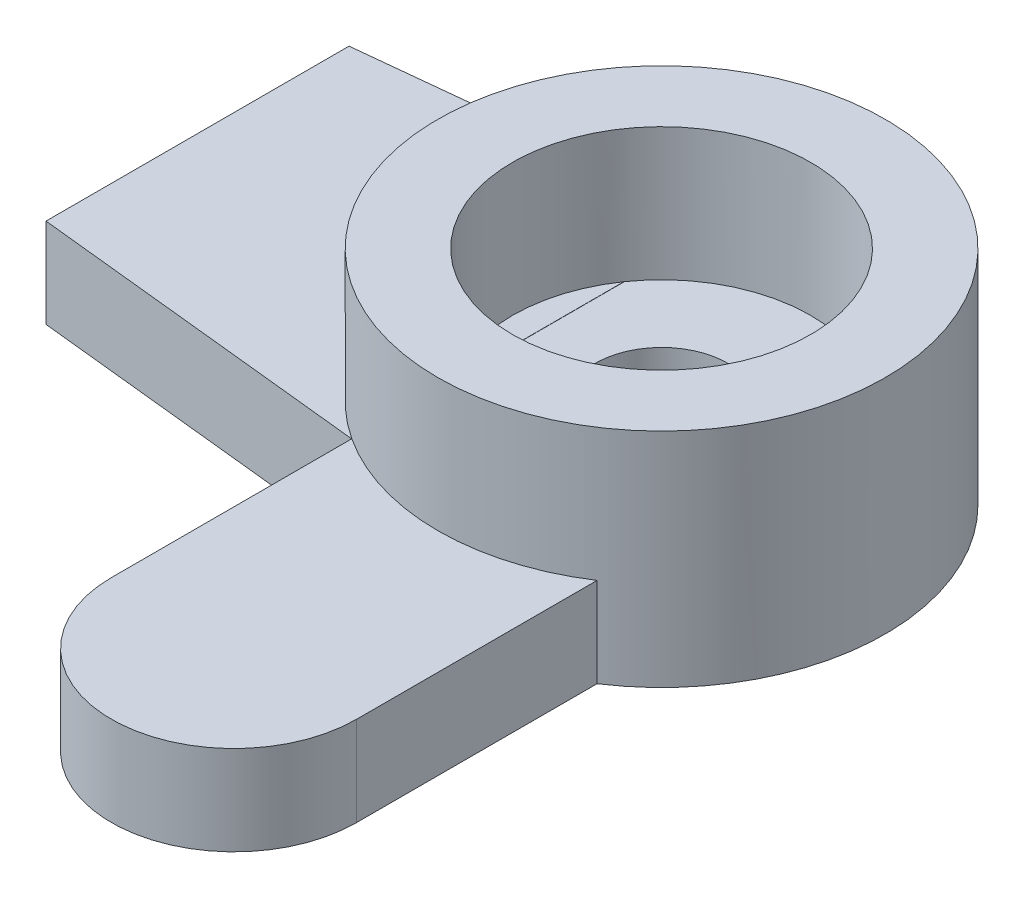
SolidWorks part; units mm, degrees
ref_plane "Piano frontale" through (0, 0, 0) normal (0, 0, 1) x (1, 0, 0)
ref_plane "Piano superiore" through (0, 0, 0) normal (0, 1, 0) x (1, 0, 0)
ref_plane "Piano destro" through (0, 0, 0) normal (1, 0, 0) x (0, 0, -1)
sketch "Schizzo1" plane through (0, 0, 0) normal (0, 1, 0) x (1, 0, 0)
  line L0 (-1.8466, 2.825) -> (-14.5, 1.5)
  line L1 (-1.8466, -2.825) -> (-14.5, -1.5)
  line L2 (-1.8466, 2.825) -> (-1.8466, -2.825)
  line L3 (0, -6.45) -> (0, 6.45) construction
  line L4 (1.85, 3.45) -> (1.85, -3.45)
  line L5 (1.85, -3.45) -> (16.7, -1.5)
  line L6 (1.85, 3.45) -> (16.7, 1.5)
  line L7 (-1.85, -6.45) -> (-1.85, 6.45)
  line L8 (1.85, -6.45) -> (1.85, 6.45)
  line L9 (-7, -2.2854) -> (-7, 2.2854)
  circle A0 centre (0, 0) radius 3.375
  arc A1 (-14.5, 1.5) -> (-14.5, -1.5) centre (-14.5, 0) ccw
  arc A2 (16.7, 1.5) -> (16.7, -1.5) centre (16.7, 0) cw
  arc A3 (-1.85, -6.45) -> (1.85, -6.45) centre (0, -6.45) ccw
  arc A4 (1.85, 6.45) -> (-1.85, 6.45) centre (0, 6.45) ccw
  point P8 (-1.8466, 0)
  point P14 (18.2, 0)
  point P18 (1.85, 0)
  point P19 (0, 0)
  point P25 (-16, 0)
  point P31 (0, 8.3)
  point P32 (0, -8.3)
  dimension "D1" = 6.75
  dimension "D3" = 1.5
  dimension "D7" = 1.5
  dimension "D2" = 5.65
  dimension "D4" = 3
  dimension "D5" = 16
  dimension "D6" = 6.9
  dimension "D8" = 3
  dimension "D9" = 34.2
  dimension "D10" = 3.7
  dimension "D11" = 16.6
  dimension "D12" = 7
extrude "Estrusione-Estrusione1" add sketch "Schizzo1" along normal blind 1.35
sketch "Schizzo2" plane through (0, 1.35, 0) normal (0, 1, 0) x (1, 0, 0)
  circle A0 centre (0, 0) radius 3.375
  dimension "D1" = 6.75
extrude "Estrusione-Estrusione2" add sketch "Schizzo2" along normal blind 2
sketch "Schizzo4" plane through (0, 3.35, 0) normal (0, 1, 0) x (1, 0, 0)
  circle A0 centre (0, 0) radius 2.25
  dimension "D1" = 4.5
extrude "Taglio-Estrusione1" cut sketch "Schizzo4" against normal blind 2
sketch "Schizzo5" plane through (0, 1.35, 0) normal (0, 1, 0) x (1, 0, 0)
  circle A0 centre (0, 0) radius 1
  dimension "D1" = 2
extrude "Taglio-Estrusione2" cut sketch "Schizzo5" against normal through all
